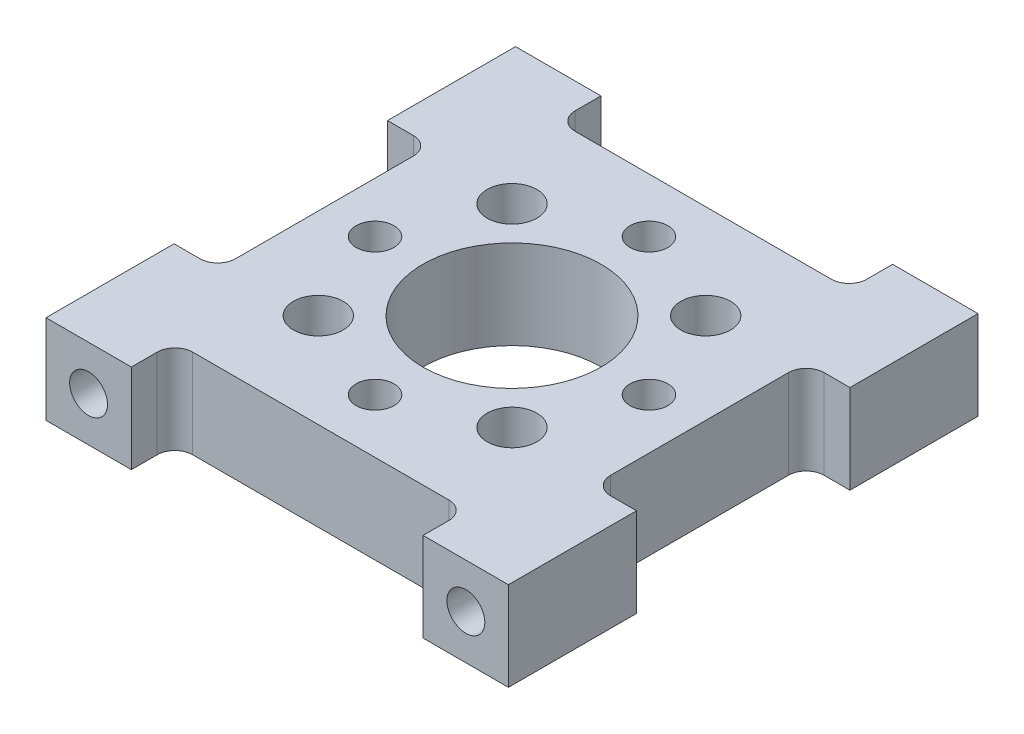
SolidWorks part; units mm, degrees
ref_plane "Front Plane" through (0, 0, 0) normal (0, 0, 1) x (1, 0, 0)
ref_plane "Top Plane" through (0, 0, 0) normal (0, 1, 0) x (1, 0, 0)
ref_plane "Right Plane" through (0, 0, 0) normal (1, 0, 0) x (0, 0, -1)
ref_plane "Plane1" through (0, 0, 0) normal (0, -1, 0) x (1, 0, 0)
sketch "Sketch1" plane through (0, 0, 0) normal (0, -1, 0) x (1, 0, 0)
  line L0 (-16.51, 16.764) -> (-16.51, -16.764)
  line L1 (-16.51, -16.764) -> (16.51, -16.764)
  line L2 (16.51, -16.764) -> (16.51, 16.764)
  line L3 (16.51, 16.764) -> (-16.51, 16.764)
extrude "Boss-Extrude1" add sketch "Sketch1" against normal blind 6.35
sketch "Sketch2" plane through (0, 6.35, 0) normal (0, 1, 0) x (-1, 0, 0)
  line L0 (-16.51, -7.62) -> (-13.3909, -7.62)
  line L1 (-13.3909, -7.62) -> (-13.3909, 7.62)
  line L2 (-13.3909, 7.62) -> (-16.51, 7.62)
  line L3 (-16.51, 7.62) -> (-16.51, -7.62)
extrude "Cut-Extrude1" cut sketch "Sketch2" against normal through all
sketch "Sketch3" plane through (0, 6.35, 0) normal (0, 1, 0) x (-1, 0, 0)
  line L0 (-10.414, 16.764) -> (-10.414, 13.6525)
  line L1 (-10.414, 13.6525) -> (10.414, 13.6525)
  line L2 (10.414, 13.6525) -> (10.414, 16.764)
  line L3 (10.414, 16.764) -> (-10.414, 16.764)
extrude "Cut-Extrude2" cut sketch "Sketch3" against normal through all
sketch "Sketch4" plane through (0, 6.35, 0) normal (0, 1, 0) x (-1, 0, 0)
  line L0 (16.51, 7.62) -> (13.3909, 7.62)
  line L1 (13.3909, 7.62) -> (13.3909, -7.62)
  line L2 (13.3909, -7.62) -> (16.51, -7.62)
  line L3 (16.51, -7.62) -> (16.51, 7.62)
extrude "Cut-Extrude3" cut sketch "Sketch4" against normal through all
sketch "Sketch5" plane through (0, 6.35, 0) normal (0, 1, 0) x (-1, 0, 0)
  line L0 (10.414, -16.764) -> (10.414, -13.6525)
  line L1 (10.414, -13.6525) -> (-10.414, -13.6525)
  line L2 (-10.414, -13.6525) -> (-10.414, -16.764)
  line L3 (-10.414, -16.764) -> (10.414, -16.764)
extrude "Cut-Extrude4" cut sketch "Sketch5" against normal through all
hole_wizard "Hole1" positions "Sketch7" profile "Sketch6" legacy
sketch "Sketch7" plane through (0, 6.35, 0) normal (0, 1, 0) x (1, 0, 0)
  point P0 (0, 0)
sketch "Sketch6" plane through (0, 6.35, 0) normal (1, 0, 0) x (0, 0, 1)
  line L0 (0, 0) -> (0, 6.35)
  line L1 (0, 6.35) -> (6.3627, 6.35)
  line L2 (6.3627, 6.35) -> (6.3627, 0)
  line L3 (6.3627, 0) -> (0, 0)
  line L4 (0, 110) -> (0, -10) construction
  dimension "Diameter" = 12.7254
  dimension "Depth" = 6.35
hole_wizard "M2.5 Clearance Hole1" positions "Sketch9" profile "Sketch8" hole size "M2.5" standard "ANSI Metric"
sketch "Sketch9" plane through (0, 6.35, 0) normal (0, 1, 0) x (1, 0, 0)
  point P0 (0, 9.779)
  point P1 (9.779, 0)
  point P2 (0, -9.779)
  point P3 (-9.779, 0)
sketch "Sketch8" plane through (0, 6.35, -9.779) normal (1, 0, 0) x (0, 0, 1)
  line L0 (0, 0) -> (0, 6.35)
  line L1 (0, 6.35) -> (1.3525, 6.35)
  line L2 (1.3525, 6.35) -> (1.3525, 0)
  line L5 (1.3525, 0) -> (0, 0)
  line L11 (0, -6.35) -> (0, 107.95) construction
  dimension "Thru Hole Dia." = 2.7051
  dimension "Thru Hole Depth" = 6.35
hole_wizard "M3 Clearance Hole1" positions "Sketch11" profile "Sketch10" hole size "M3" standard "ANSI Metric"
sketch "Sketch11" plane through (0, 6.35, 0) normal (0, 1, 0) x (1, 0, 0)
  point P0 (-6.9148, -6.9148)
  point P1 (6.9148, -6.9148)
  point P2 (6.9148, 6.9148)
  point P3 (-6.9148, 6.9148)
sketch "Sketch10" plane through (-6.9148, 6.35, 6.9148) normal (1, 0, 0) x (0, 0, 1)
  line L0 (0, 0) -> (0, 6.35)
  line L1 (0, 6.35) -> (1.778, 6.35)
  line L2 (1.778, 6.35) -> (1.778, 0)
  line L5 (1.778, 0) -> (0, 0)
  line L11 (0, -6.35) -> (0, 107.95) construction
  dimension "Thru Hole Dia." = 3.556
  dimension "Thru Hole Depth" = 6.35
hole_wizard "M2.5 Clearance Hole2" positions "Sketch13" profile "Sketch12" hole size "M2.5" standard "ANSI Metric"
sketch "Sketch13" plane through (0, 0, -16.764) normal (0, 0, -1) x (-1, 0, 0)
  point P0 (13.4704, 3.175)
  point P1 (-13.4704, 3.175)
sketch "Sketch12" plane through (-13.4704, 3.175, -16.764) normal (1, 0, 0) x (0, 1, 0)
  line L0 (0, 0) -> (0, 8.4327)
  line L1 (0, 8.4327) -> (1.3525, 7.62)
  line L2 (1.3525, 7.62) -> (1.3525, 0)
  line L5 (1.3525, 0) -> (0, 0)
  line L10 (0, 8.4327) -> (-1.3525, 7.62) construction
  line L11 (0, -6.35) -> (0, 107.95) construction
  dimension "Hole Dia." = 2.7051
  dimension "Hole Depth" = 7.62
  dimension "Drill Angle" = 118
hole_wizard "M2.5 Clearance Hole3" positions "Sketch15" profile "Sketch14" hole size "M2.5" standard "ANSI Metric"
sketch "Sketch15" plane through (0, 0, 16.764) normal (0, 0, 1) x (1, 0, 0)
  point P0 (13.4704, 3.175)
  point P1 (-13.4704, 3.175)
sketch "Sketch14" plane through (13.4704, 3.175, 16.764) normal (1, 0, 0) x (0, -1, 0)
  line L0 (0, 0) -> (0, 8.4327)
  line L1 (0, 8.4327) -> (1.3525, 7.62)
  line L2 (1.3525, 7.62) -> (1.3525, 0)
  line L5 (1.3525, 0) -> (0, 0)
  line L10 (0, 8.4327) -> (-1.3525, 7.62) construction
  line L11 (0, -6.35) -> (0, 107.95) construction
  dimension "Hole Dia." = 2.7051
  dimension "Hole Depth" = 7.62
  dimension "Drill Angle" = 118
fillet "Fillet1" radius 1.27 8 edges at (10.414, 3.175, -13.6525) (-13.3909, 3.175, -7.62) (-13.3909, 3.175, 7.62) (13.3909, 3.175, 7.62) (-10.414, 3.175, -13.6525) (10.414, 3.175, 13.6525) (13.3909, 3.175, -7.62) (-10.414, 3.175, 13.6525)
